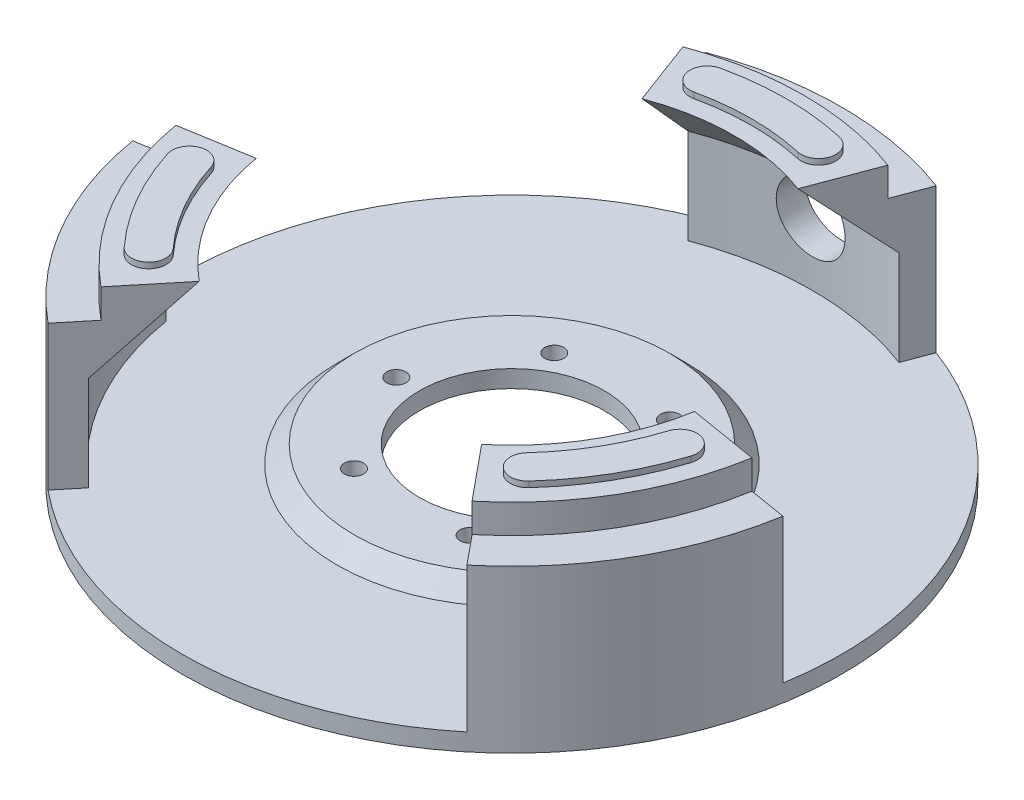
SolidWorks part; units mm, degrees
ref_plane "Front Plane" through (0, 0, 0) normal (0, 0, 1) x (1, 0, 0)
ref_plane "Top Plane" through (0, 0, 0) normal (0, 1, 0) x (1, 0, 0)
ref_plane "Right Plane" through (0, 0, 0) normal (1, 0, 0) x (0, 0, -1)
sketch "Sketch1" plane through (0, 0, 0) normal (0, 0, 1) x (1, 0, 0)
  line L1 (50.5, 19) -> (50.5, 14)
  line L2 (50.5, 14) -> (57, 14)
  line L3 (57, 14) -> (57, -14)
  line L4 (57, -14) -> (26, -14)
  line L5 (26, -14) -> (26, -11)
  line L7 (52, -11) -> (52, 5.4289)
  line L10 (0, 34.2778) -> (0, -25.6111) construction
  line L13 (38.4289, 19) -> (52, 5.4289)
  line L14 (26, -11) -> (16, -11)
  line L15 (16, -11) -> (16, -8)
  line L16 (16, -8) -> (27.2426, -8)
  line L17 (27.2426, -8) -> (30.2426, -11)
  line L18 (30.2426, -11) -> (52, -11)
  line L19 (38.4289, 19) -> (50.5, 19)
  point P0 (31.3769, 19)
  point P12 (57, 0)
  dimension "D1" = 3
  dimension "D2" = 5
  dimension "D3" = 114
  dimension "D4" = 101
  dimension "D5" = 30
  dimension "D6" = 5
  dimension "D7" = 45
  dimension "D8" = 3
  dimension "D9" = 5
  dimension "D10" = 52
  dimension "D12" = 10
  dimension "D13" = 3
revolve "Revolve1" add sketch "Sketch1" angle 360 about L10
sketch "Sketch2" plane through (0, -11, 0) normal (0, 1, 0) x (1, 0, 0)
  line L2 (20, 53.376) -> (-20, 53.376) construction
  line L3 (56.225, -9.3675) -> (36.225, -44.0085) construction
  line L4 (0, 0) -> (36.225, -44.0085) construction
  line L5 (20, 53.376) -> (12.9825, 34.6476)
  line L6 (56.225, -9.3675) -> (36.4969, -6.0807)
  circle A0 centre (0, 0) radius 57 construction
  arc A1 (20, 53.376) -> (56.225, -9.3675) centre (0, 0) cw
  arc A2 (12.9825, 34.6476) -> (36.4969, -6.0807) centre (0, 0) cw
  point P11 (0, 0)
  dimension "D1" = 40
  dimension "D2" = 120
  dimension "D3" = 20
extrude "Cut-Extrude1" cut sketch "Sketch2" along normal through all
pattern_circular "CirPattern1" count 3 over 360 about axis through (0, 0, 0) along (0, 1, 0) of "Cut-Extrude1"
sketch "Sketch3" plane through (0, 19, 0) normal (0, 1, 0) x (1, 0, 0)
  line L0 (-13.4838, 35.9857) -> (-17.7193, 47.2893) construction
  line L1 (-9.6239, 43.4105) -> (0, 0) construction
  line L2 (0, 0) -> (9.6239, 43.4105) construction
  arc A0 (-9.6239, 43.4105) -> (9.6239, 43.4105) centre (0, 0) cw construction
  arc A1 (10.2732, 46.3394) -> (-10.2732, 46.3394) centre (0, 0) ccw
  arc A2 (8.9746, 40.4816) -> (-8.9746, 40.4816) centre (0, 0) ccw
  arc A3 (8.9746, 40.4816) -> (10.2732, 46.3394) centre (9.6239, 43.4105) ccw
  arc A4 (-10.2732, 46.3394) -> (-8.9746, 40.4816) centre (-9.6239, 43.4105) ccw
  point P4 (0, 44.4645)
  point P16 (-15.6016, 41.6375)
  dimension "D1" = 3
  dimension "D2" = 25
  dimension "D3" = 44.4645
extrude "Boss-Extrude1" add sketch "Sketch3" along normal blind 1
pattern_circular "CirPattern2" count 3 over 360 about axis through (0, 0, 0) along (0, 1, 0) of "Boss-Extrude1"
sketch "Sketch4" plane through (0, -8, 0) normal (0, 1, 0) x (1, 0, 0)
  circle A0 centre (20, 0) radius 1.65
  point P2 (0, 0)
  point P4 (0, 0)
  point P5 (0, 0)
  dimension "D1" = 3.3
  dimension "D2" = 20
extrude "Cut-Extrude2" cut sketch "Sketch4" against normal through all
pattern_circular "CirPattern3" count 6 over 360 about axis through (0, 0, 0) along (0, 1, 0) of "Cut-Extrude2"
sketch "Sketch5" plane through (0, 0, 0) normal (0, 0, 1) x (1, 0, 0)
  circle A0 centre (0, 0) radius 5.95
  dimension "D1" = 11.9
extrude "Cut-Extrude3" cut sketch "Sketch5" against normal through all
